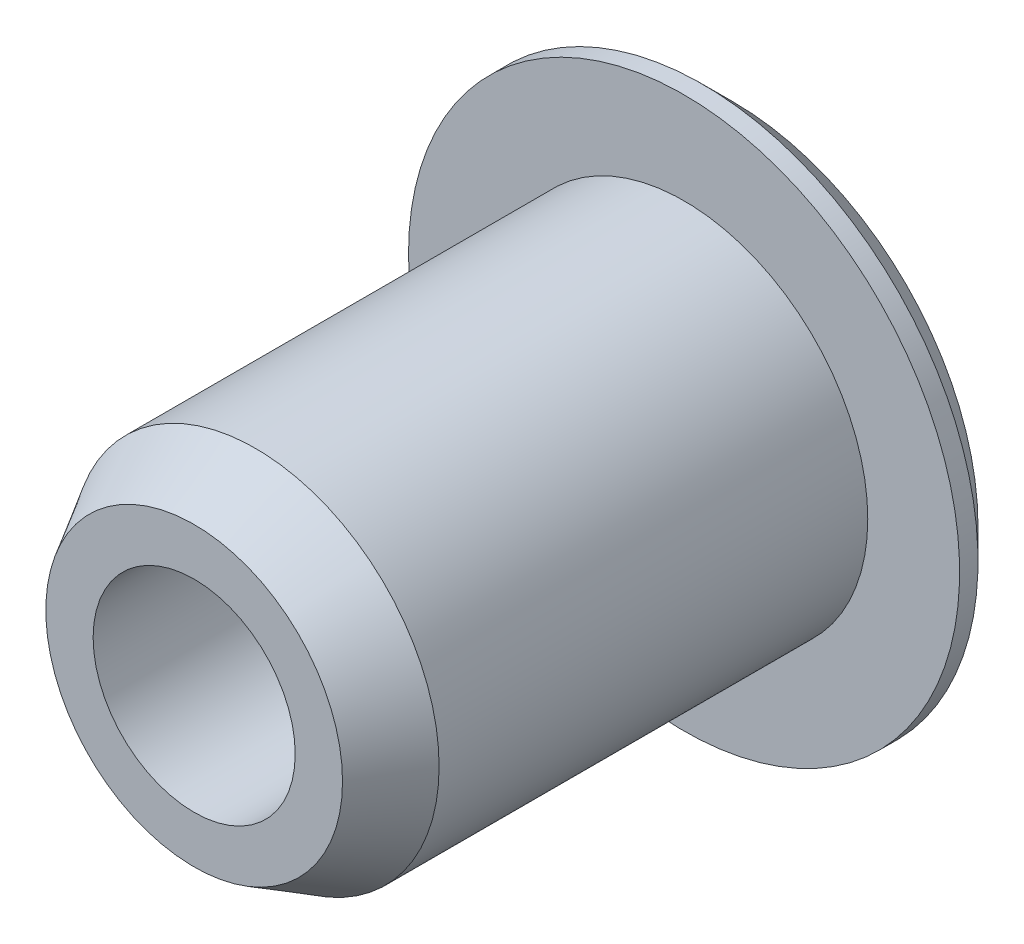
SolidWorks part; units mm, degrees
ref_plane "前视基准面" through (0, 0, 0) normal (0, 0, 1) x (1, 0, 0)
ref_plane "上视基准面" through (0, 0, 0) normal (0, 1, 0) x (1, 0, 0)
ref_plane "右视基准面" through (0, 0, 0) normal (1, 0, 0) x (0, 0, -1)
sketch "草图1" plane through (0, 0, 0) normal (0, 0, 1) x (1, 0, 0)
  circle A1 centre (0, 0) radius 1.65
  circle A2 centre (0, 0) radius 3
  dimension "内径" = 3.3
  dimension "外径" = 6
extrude "凸台-拉伸1" add sketch "草图1" along normal blind 8
sketch "草图2" plane through (0, 0, 0) normal (0, 0, -1) x (-1, 0, 0)
  circle A0 centre (0, 0) radius 4.5
  circle A1 centre (0, 0) radius 1.65 construction
  circle A3 centre (0, 0) radius 1.65
  dimension "外径" = 9
extrude "凸台-拉伸2" add sketch "草图2" along normal blind 0.8
sketch "草图3" plane through (0, 0, -0.8) normal (0, 0, -1) x (-1, 0, 0)
  circle A0 centre (0, 0) radius 2.2
  circle A1 centre (0, 0) radius 3 construction
  dimension "D1" = 0.8
extrude "切除-拉伸1" cut sketch "草图3" against normal blind 3
chamfer "倒角1" distance 0.5 angle 45 1 edges at (-4.5, 0, -0.8)
chamfer "倒角2" distance 1 angle 30 1 edges at (3, 0, 8)
